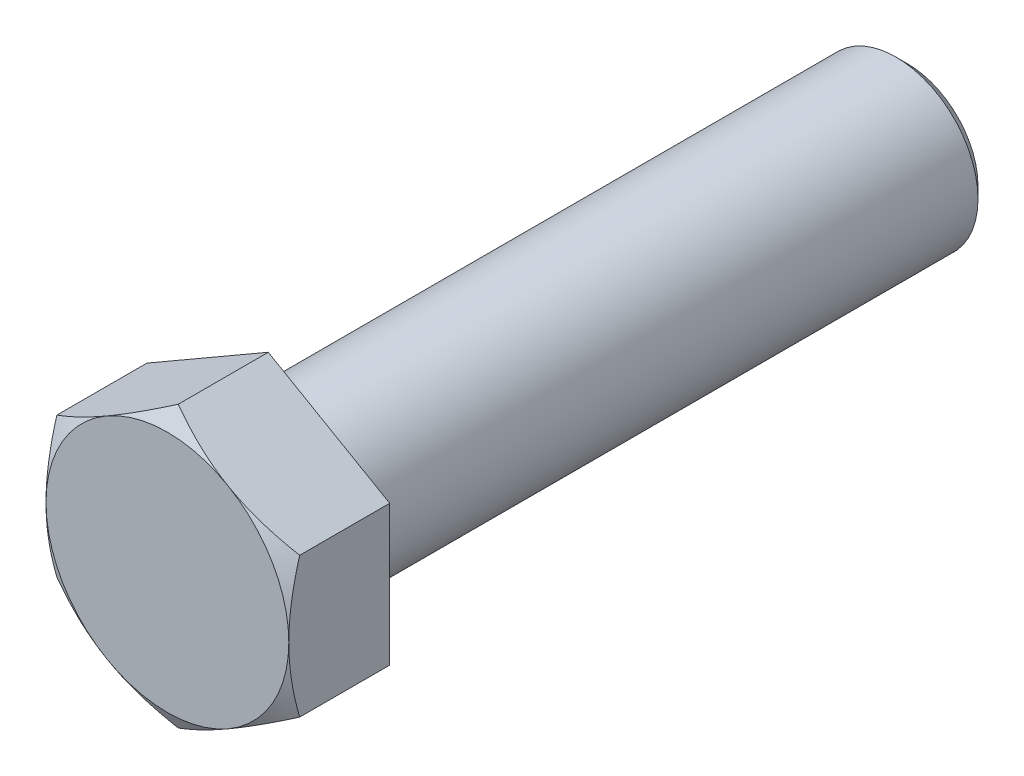
SolidWorks part; units mm, degrees
ref_plane "Front Plane" through (0, 0, 0) normal (0, 0, 1) x (1, 0, 0)
ref_plane "Top Plane" through (0, 0, 0) normal (0, 1, 0) x (1, 0, 0)
ref_plane "Right Plane" through (0, 0, 0) normal (1, 0, 0) x (0, 0, -1)
sketch "Sketch1" plane through (0, 0, 0) normal (0, 0, 1) x (1, 0, 0)
  line L0 (0, 0) -> (0, 15.3979) construction
  line L2 (0, 15.3979) -> (-13.335, 7.699)
  line L3 (-13.335, 7.699) -> (-13.335, -7.699)
  line L4 (-13.335, -7.699) -> (0, -15.3979)
  line L5 (0, -15.3979) -> (13.335, -7.699)
  line L6 (13.335, -7.699) -> (13.335, 7.699)
  line L7 (13.335, 7.699) -> (0, 15.3979)
  circle A0 centre (0, 0) radius 13.335 construction
  dimension "HEX" = 26.67
extrude "Boss-Extrude1" add sketch "Sketch1" along normal blind 11.28
sketch "Sketch2" plane through (0, 0, 0) normal (1, 0, 0) x (0, 0, -1)
  line L0 (0, 0) -> (70, 0) construction
  line L1 (0, 0) -> (0, 9.6)
  line L4 (68.75, 9) -> (70, 7.75)
  line L7 (70, 7.75) -> (70, 0)
  line L8 (70, 0) -> (0, 0)
  line L9 (68.75, 9) -> (0.6, 9)
  arc A3 (0.6, 9) -> (0, 9.6) centre (0.6, 9.6) cw
  dimension "D1" = 0.6
  dimension "LENGTH" = 70
  dimension "WIDTH2" = 15.5
  dimension "WIDTH1" = 18
  dimension "D5" = 45
revolve "Revolve1" add sketch "Sketch2" angle 360 about L0
cosmetic thread "Cosmetic Thread1" parameters "D1"=42, "D2"=18
sketch "Sketch3" plane through (0, 0, 0) normal (1, 0, 0) x (0, 0, -1)
  line L0 (-12.2049, 0) -> (129.7862, 0) construction
  line L1 (-11.28, 15.3979) -> (-10.089, 15.3979)
  line L2 (-0.2, 15.3979) -> (-0.2, 12.7655)
  line L3 (-10.089, 15.3979) -> (-11.28, 13.335)
  line L4 (-0.2, 12.7655) -> (0, 12.65)
  line L5 (-11.28, 13.335) -> (-11.28, 15.3979)
  line L6 (0, -7.699) -> (0, 7.699) construction
  line L7 (-11.28, 15.3979) -> (0, 15.3979) construction
  line L8 (-11.28, 7.699) -> (-11.28, 15.3979) construction
  line L10 (0, 12.65) -> (0, 15.3979)
  line L11 (0, 15.3979) -> (-0.2, 15.3979)
  dimension "D1" = 30
  dimension "SAME AS HEX" = 26.67
  dimension "D3" = 30
  dimension "C" = 0.2
  dimension "DW" = 25.3
revolve "Cut-Revolve1" cut sketch "Sketch3" angle 360 about L0
